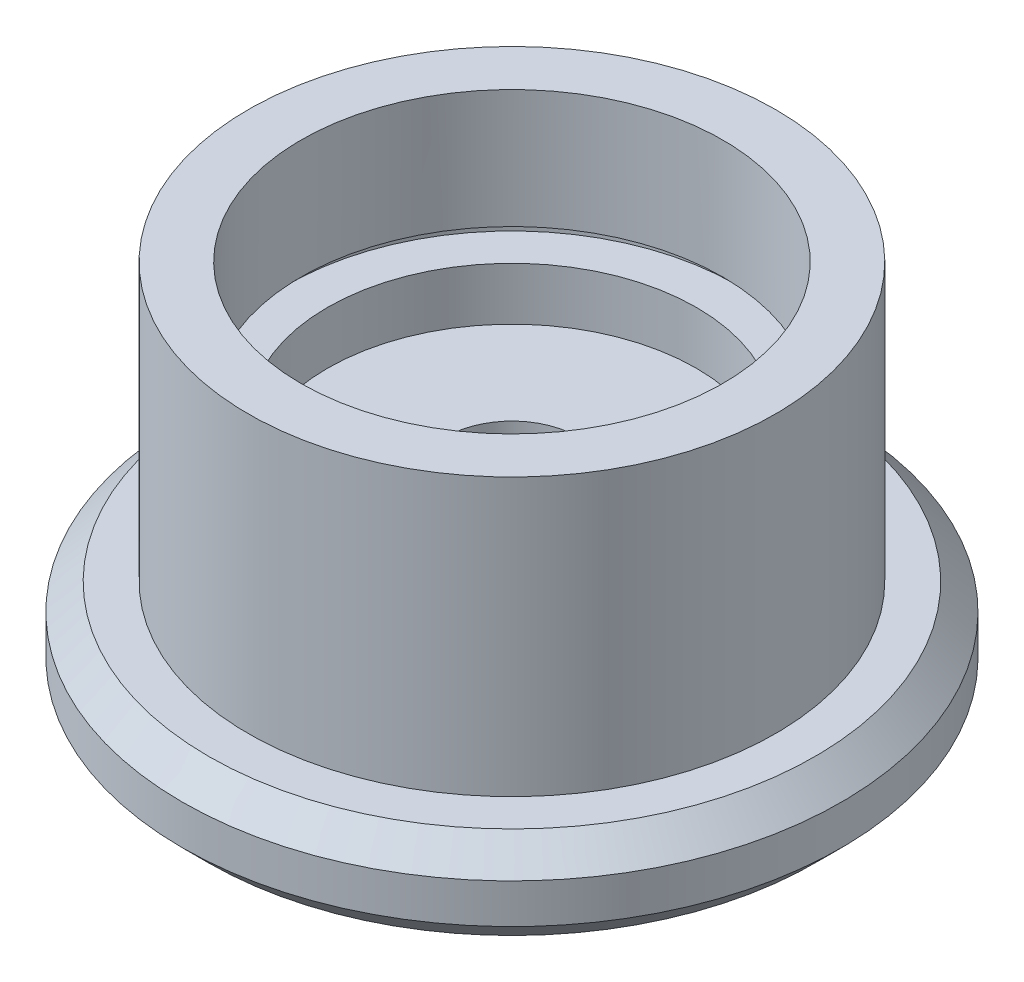
SolidWorks part; units mm, degrees
ref_plane "Plan de face" through (0, 0, 0) normal (0, 0, 1) x (1, 0, 0)
ref_plane "Plan de dessus" through (0, 0, 0) normal (0, 1, 0) x (1, 0, 0)
ref_plane "Plan de droite" through (0, 0, 0) normal (1, 0, 0) x (0, 0, -1)
sketch "Esquisse1" plane through (0, 0, 0) normal (0, 1, 0) x (1, 0, 0)
  circle A0 centre (0, 0) radius 12.5
  dimension "D1" = 25
extrude "Boss.-Extru.1" add sketch "Esquisse1" along normal blind 3.5
sketch "Esquisse2" plane through (0, 3.5, 0) normal (0, 1, 0) x (1, 0, 0)
  circle A0 centre (0, 0) radius 10
  dimension "D1" = 20
extrude "Boss.-Extru.2" add sketch "Esquisse2" along normal blind 10.5
sketch "Esquisse3" plane through (0, 0, 0) normal (0, -1, 0) x (1, 0, 0)
  circle A0 centre (0, 0) radius 2.5
  dimension "D1" = 5
extrude "Enlèv. mat.-Extru.1" cut sketch "Esquisse3" against normal blind 7
sketch "Esquisse4" plane through (0, 7, 0) normal (0, -1, 0) x (1, 0, 0)
  circle A0 centre (0, 0) radius 7
  dimension "D1" = 14
extrude "Enlèv. mat.-Extru.2" cut sketch "Esquisse4" against normal blind 2
sketch "Esquisse5" plane through (0, 9, 0) normal (0, -1, 0) x (1, 0, 0)
  circle A0 centre (0, 0) radius 8.5
  dimension "D1" = 17
extrude "Enlèv. mat.-Extru.3" cut sketch "Esquisse5" against normal blind 0.5
sketch "Esquisse6" plane through (0, 14, 0) normal (0, 1, 0) x (1, 0, 0)
  circle A0 centre (0, 0) radius 8
  dimension "D1" = 16
extrude "Enlèv. mat.-Extru.4" cut sketch "Esquisse6" against normal blind 5
chamfer "Chanfrein1" distance 1 angle 45 1 edges at (0, 3.5, 12.5)
chamfer "Chanfrein2" distance 1 angle 45 1 edges at (0, 0, 12.5)
